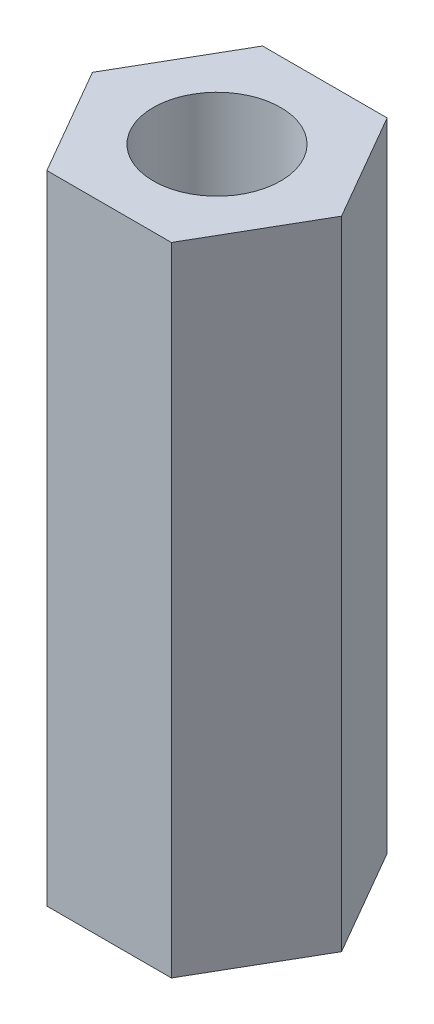
SolidWorks part; units mm, degrees
material "Nylon 101"
ref_plane "Front Plane" through (0, 0, 0) normal (0, 0, 1) x (1, 0, 0)
ref_plane "Top Plane" through (0, 0, 0) normal (0, 1, 0) x (1, 0, 0)
ref_plane "Right Plane" through (0, 0, 0) normal (1, 0, 0) x (0, 0, -1)
sketch "Sketch1" plane through (0, 0, 0) normal (0, 1, 0) x (1, 0, 0)
  line L0 (0, 0) -> (50000, 0) construction
  line L1 (0, 0) -> (0, 50000) construction
  line L2 (1.4665, 2.54) -> (-1.4665, 2.54)
  line L3 (-1.4665, 2.54) -> (-2.9329, 0)
  line L4 (1.4665, 2.54) -> (2.9329, 0)
  line L5 (1.4665, -2.54) -> (2.9329, 0)
  line L6 (-1.4665, -2.54) -> (-2.9329, 0)
  line L7 (1.4665, -2.54) -> (-1.4665, -2.54)
  circle A0 centre (0, 0) radius 1.5
  point P11 (0, 2.54)
  point P14 (0, -2.54)
  point P15 (-1.7951, 3.1605)
  point P16 (1.9986, 3.9568)
  dimension "D1" = 3
  dimension "D2" = 5.08
  dimension "D3" = 5.08
extrude "Boss-Extrude1" add sketch "Sketch1" along normal blind 15
equation "\"D3@Sketch1\"=\"D2@Sketch1\""
